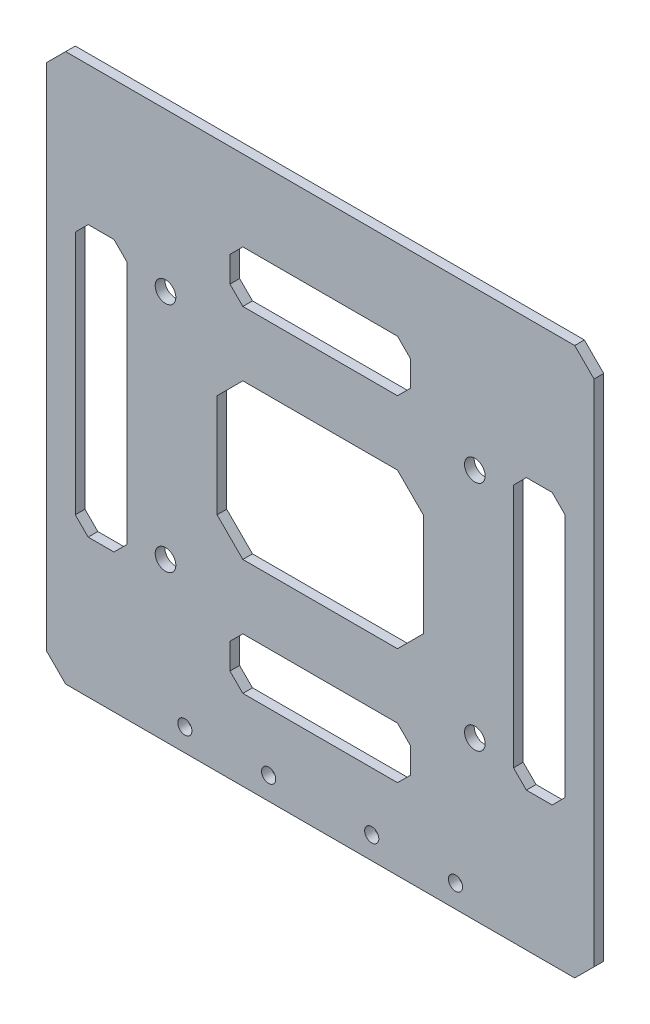
SolidWorks part; units mm, degrees
material "碳纤维板_1600kg_m3"
ref_plane "前视基准面" through (0, 0, 0) normal (0, 0, 1) x (1, 0, 0)
ref_plane "上视基准面" through (0, 0, 0) normal (0, 1, 0) x (1, 0, 0)
ref_plane "右视基准面" through (0, 0, 0) normal (1, 0, 0) x (0, 0, -1)
other "Configuration Table"
sketch "草图1" plane through (0, 0, 0) normal (0, 0, 1) x (1, 0, 0)
  line L0 (-42.5, -39.5) -> (-39.5, -42.5)
  line L1 (-39.5, -42.5) -> (39.5, -42.5)
  line L2 (39.5, -42.5) -> (42.5, -39.5)
  line L3 (42.5, -39.5) -> (42.5, 39.5)
  line L4 (42.5, 39.5) -> (39.5, 42.5)
  line L5 (39.5, 42.5) -> (-39.5, 42.5)
  line L6 (-39.5, 42.5) -> (-42.5, 39.5)
  line L7 (-42.5, 39.5) -> (-42.5, -39.5)
  circle A0 centre (-24, -18) radius 1.6
  circle A1 centre (-24, 18) radius 1.6
  circle A2 centre (24, -18) radius 1.6
  circle A3 centre (24, 18) radius 1.6
  circle A4 centre (-21, -39) radius 1.1
  circle A5 centre (-8, -39) radius 1.1
  circle A6 centre (8, -39) radius 1.1
  circle A7 centre (21, -39) radius 1.1
extrude "85方雷达盖板_1p5mm" add sketch "草图1" along normal blind 1.5
sketch "草图4" plane through (0, 0, 0) normal (0, 0, 1) x (1, 0, 0)
  line L0 (-12, -12) -> (12, -12)
  line L1 (12, -12) -> (16, -8)
  line L2 (16, -8) -> (16, 8)
  line L3 (16, 8) -> (12, 12)
  line L4 (12, 12) -> (-12, 12)
  line L5 (-12, 12) -> (-16, 8)
  line L6 (-16, 8) -> (-16, -8)
  line L7 (-16, -8) -> (-12, -12)
  line L8 (-32, -21) -> (-36, -21)
  line L9 (-36, -21) -> (-38, -19)
  line L10 (-38, -19) -> (-38, 19)
  line L11 (-38, 19) -> (-36, 21)
  line L12 (-36, 21) -> (-32, 21)
  line L13 (-32, 21) -> (-30, 19)
  line L14 (-30, 19) -> (-30, -19)
  line L15 (-30, -19) -> (-32, -21)
  line L16 (32, -21) -> (36, -21)
  line L17 (36, -21) -> (38, -19)
  line L18 (38, -19) -> (38, 19)
  line L19 (38, 19) -> (36, 21)
  line L20 (36, 21) -> (32, 21)
  line L21 (32, 21) -> (30, 19)
  line L22 (30, 19) -> (30, -19)
  line L23 (30, -19) -> (32, -21)
  line L24 (-12, -22) -> (12, -22)
  line L25 (12, -22) -> (14, -24)
  line L26 (14, -24) -> (14, -28)
  line L27 (14, -28) -> (12, -30)
  line L28 (12, -30) -> (-12, -30)
  line L29 (-12, -30) -> (-14, -28)
  line L30 (-14, -28) -> (-14, -24)
  line L31 (-14, -24) -> (-12, -22)
  line L32 (-12, 22) -> (12, 22)
  line L33 (12, 22) -> (14, 24)
  line L34 (14, 24) -> (14, 28)
  line L35 (14, 28) -> (12, 30)
  line L36 (12, 30) -> (-12, 30)
  line L37 (-12, 30) -> (-14, 28)
  line L38 (-14, 28) -> (-14, 24)
  line L39 (-14, 24) -> (-12, 22)
extrude "雷达托板几何镂空_中央及四向窗口" cut sketch "草图4" along normal blind 1.5
